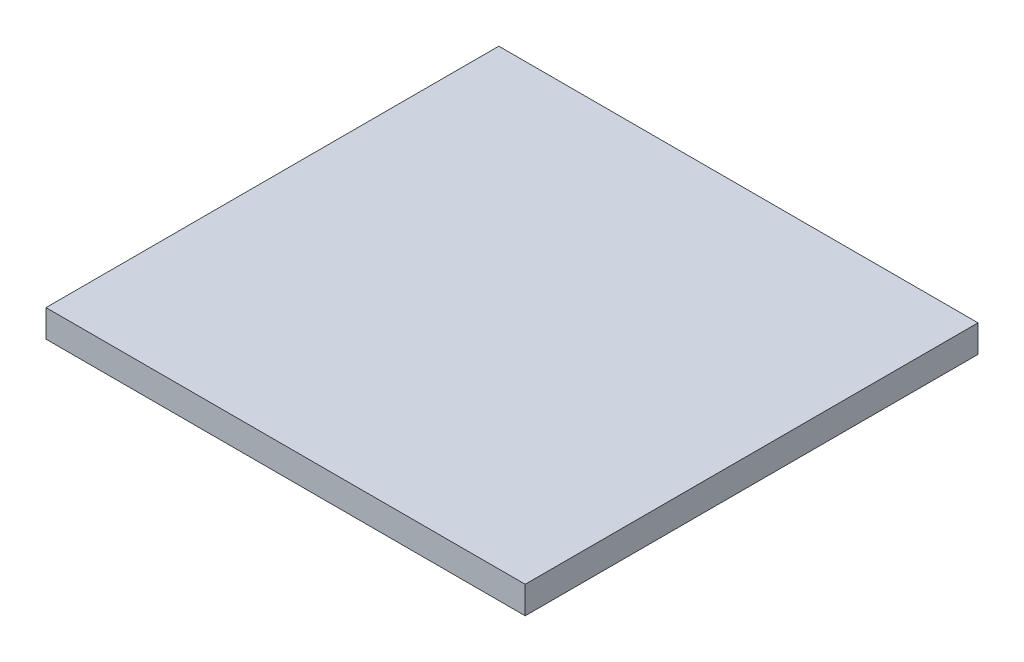
SolidWorks part; units mm, degrees
ref_plane "Front Plane" through (0, 0, 0) normal (0, 0, 1) x (1, 0, 0)
ref_plane "Top Plane" through (0, 0, 0) normal (0, 1, 0) x (1, 0, 0)
ref_plane "Right Plane" through (0, 0, 0) normal (1, 0, 0) x (0, 0, -1)
sketch "Sketch1" plane through (0, 0, 0) normal (0, 1, 0) x (1, 0, 0)
  line L1 (104.1663, 98.425) -> (-104.1663, 98.425)
  line L2 (104.1663, 98.425) -> (104.1663, -98.425)
  line L3 (104.1663, -98.425) -> (-104.1663, -98.425)
  line L4 (-104.1663, 98.425) -> (-104.1663, -98.425)
  line L5 (0, -98.425) -> (0, 98.425) construction
  line L6 (104.1663, 0) -> (-104.1663, 0) construction
  point P0 (0, 0)
  dimension "D1" = 208.3326
  dimension "D2" = 196.85
extrude "Boss-Extrude1" add sketch "Sketch1" along normal blind 11.8872
